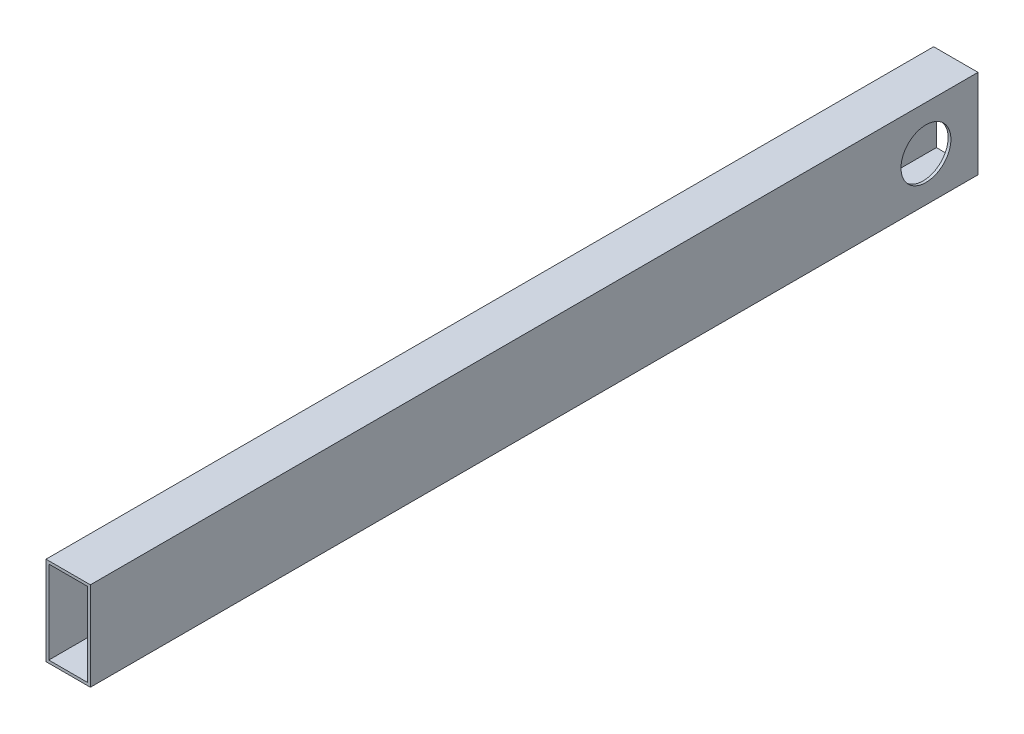
SolidWorks part; units mm, degrees
ref_plane "Front Plane" through (0, 0, 0) normal (0, 0, 1) x (1, 0, 0)
ref_plane "Top Plane" through (0, 0, 0) normal (0, 1, 0) x (1, 0, 0)
ref_plane "Right Plane" through (0, 0, 0) normal (1, 0, 0) x (0, 0, -1)
sketch "Sketch1" plane through (0, 0, 0) normal (0, 0, 1) x (1, 0, 0)
  line L0 (11.1125, -23.8125) -> (11.1125, 23.8125)
  line L1 (-12.7, -25.4) -> (12.7, -25.4)
  line L2 (-12.7, -25.4) -> (-12.7, 25.4)
  line L3 (-12.7, 25.4) -> (12.7, 25.4)
  line L4 (12.7, -25.4) -> (12.7, 25.4)
  line L5 (-12.7, -25.4) -> (12.7, 25.4) construction
  line L6 (-12.7, 25.4) -> (12.7, -25.4) construction
  line L7 (-11.1125, 23.8125) -> (11.1125, 23.8125)
  line L8 (-11.1125, -23.8125) -> (-11.1125, 23.8125)
  line L9 (-11.1125, -23.8125) -> (11.1125, -23.8125)
  point P0 (0, 0)
  dimension "D1" = 25.4
  dimension "D2" = 50.8
  dimension "D3" = 1.5875
extrude "Boss-Extrude1" add sketch "Sketch1" along normal mid plane 508
sketch "Sketch2" plane through (12.7, 0, 0) normal (1, 0, 0) x (0, 0, -1)
  circle A0 centre (224.2102, 0) radius 14.2875
extrude "Cut-Extrude1" cut sketch "Sketch2" against normal through all
